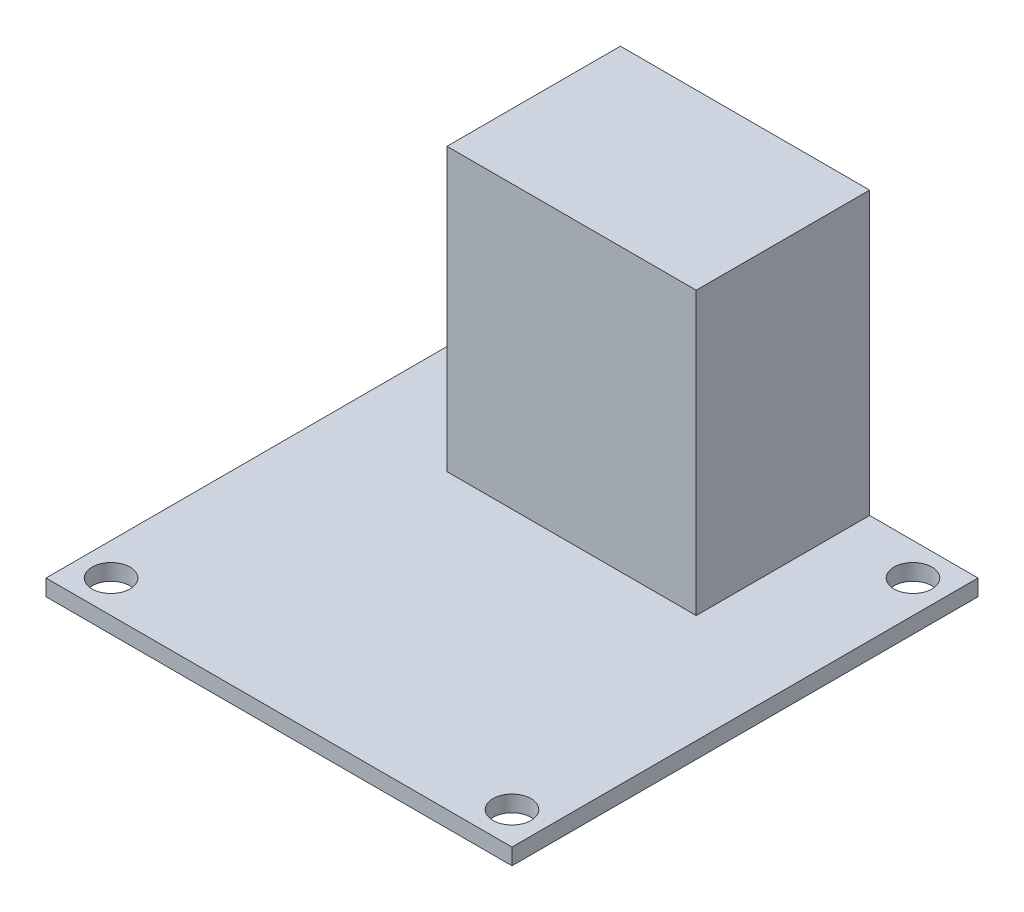
SolidWorks part; units mm, degrees
ref_plane "前视基准面" through (0, 0, 0) normal (0, 0, 1) x (1, 0, 0)
ref_plane "上视基准面" through (0, 0, 0) normal (0, 1, 0) x (1, 0, 0)
ref_plane "右视基准面" through (0, 0, 0) normal (1, 0, 0) x (0, 0, -1)
sketch "草图1" plane through (0, 0, 0) normal (0, 1, 0) x (1, 0, 0)
  line L1 (-21.5, 21.5) -> (21.5, 21.5)
  line L2 (-21.5, 21.5) -> (-21.5, -21.5)
  line L3 (-21.5, -21.5) -> (21.5, -21.5)
  line L4 (21.5, 21.5) -> (21.5, -21.5)
  line L5 (-21.5, 21.5) -> (21.5, -21.5) construction
  line L6 (-21.5, -21.5) -> (21.5, 21.5) construction
  point P0 (0, 0)
  dimension "D1" = 43
  dimension "D2" = 43
extrude "凸台-拉伸1" add sketch "草图1" along normal blind 1.5
sketch "草图2" plane through (0, 1.5, 0) normal (0, 1, 0) x (1, 0, 0)
  line L0 (0, 23.4591) -> (0, -25.7981) construction
  line L1 (-29.5819, 0) -> (26.0733, 0) construction
  circle A0 centre (-18.5, 18.5) radius 1.75
  circle A1 centre (18.5, 18.5) radius 1.75
  circle A2 centre (-18.5, -18.5) radius 1.75
  circle A3 centre (18.5, -18.5) radius 1.75
  dimension "D1" = 37
  dimension "D2" = 37
extrude "切除-拉伸1" cut sketch "草图2" against normal blind 1.5
sketch "草图3" plane through (0, 1.5, 0) normal (0, 1, 0) x (1, 0, 0)
  line L0 (0, 23.2756) -> (0, -23.677) construction
  line L1 (21.5, 21.5) -> (-21.5, 21.5) construction
  line L2 (11.5, 37.5) -> (-11.5, 37.5)
  line L3 (11.5, 37.5) -> (11.5, 5.5)
  line L4 (11.5, 5.5) -> (-11.5, 5.5)
  line L5 (-11.5, 37.5) -> (-11.5, 5.5)
  line L6 (11.5, 37.5) -> (-11.5, 5.5) construction
  line L7 (11.5, 5.5) -> (-11.5, 37.5) construction
  line L8 (-11.5, 21.5) -> (11.5, 21.5)
  point P3 (0, 21.5)
  line M10 (21.5, 21.5) -> (-21.5, 21.5)
  dimension "D1" = 23
  dimension "D2" = 32
extrude "凸台-拉伸2" add sketch "草图3" along normal blind 26 contours L5 L4 L3 M10
